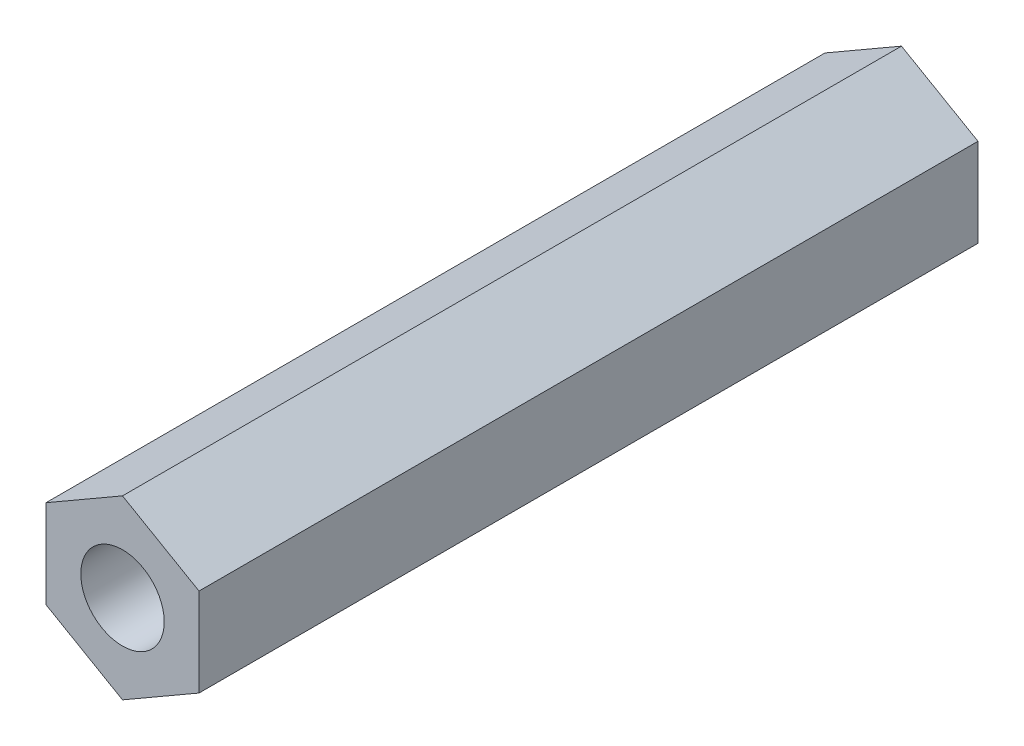
SolidWorks part; units mm, degrees
ref_plane "Plan de face" through (0, 0, 0) normal (0, 0, 1) x (1, 0, 0)
ref_plane "Plan de dessus" through (0, 0, 0) normal (0, 1, 0) x (1, 0, 0)
ref_plane "Plan de droite" through (0, 0, 0) normal (1, 0, 0) x (0, 0, -1)
sketch "Esquisse1" plane through (0, 0, 0) normal (0, 0, 1) x (1, 0, 0)
  line L1 (0, -3.1754) -> (2.75, -1.5877)
  line L2 (2.75, -1.5877) -> (2.75, 1.5877)
  line L3 (2.75, 1.5877) -> (0, 3.1754)
  line L4 (0, 3.1754) -> (-2.75, 1.5877)
  line L5 (-2.75, 1.5877) -> (-2.75, -1.5877)
  line L6 (-2.75, -1.5877) -> (0, -3.1754)
  circle A0 centre (0, 0) radius 2.75 construction
  circle A1 centre (0, 0) radius 1.5
  dimension "D2" = 3
  dimension "D1" = 5.5
extrude "Boss.-Extru.1" add sketch "Esquisse1" along normal blind 28
